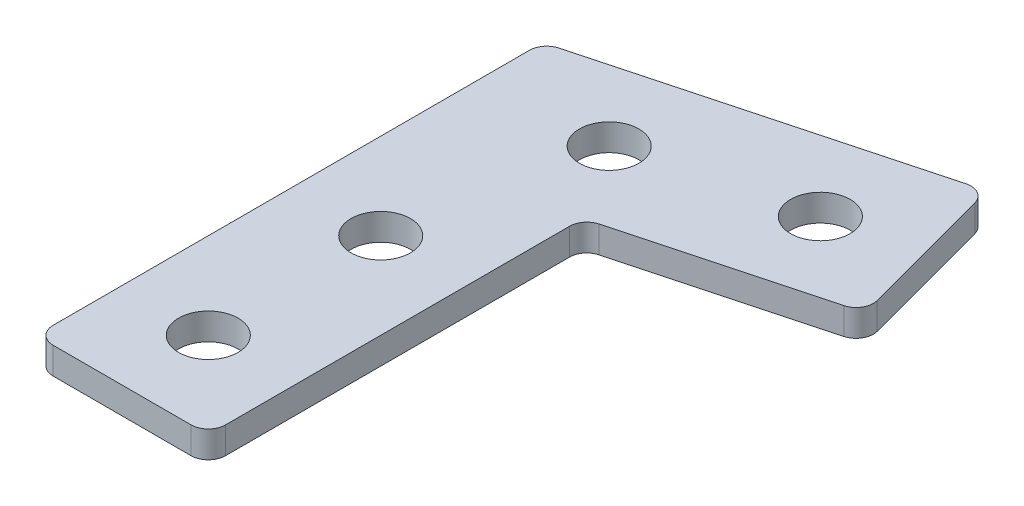
SolidWorks part; units mm, degrees
ref_plane "Front Plane" through (0, 0, 0) normal (0, 0, 1) x (1, 0, 0)
ref_plane "Top Plane" through (0, 0, 0) normal (0, 1, 0) x (1, 0, 0)
ref_plane "Right Plane" through (0, 0, 0) normal (1, 0, 0) x (0, 0, -1)
sketch "Sketch2" plane through (0, 0, 0) normal (0, 1, 0) x (1, 0, 0)
  line L0 (15.3185, 24.8356) -> (-4, 19.6593)
  line L1 (-5, 10) -> (5, 10)
  line L2 (-5, 10) -> (-5, -10)
  line L3 (-5, -10) -> (5, -10)
  line L4 (5, 10) -> (5, -10)
  line L5 (-5, 10) -> (5, -10) construction
  line L6 (-5, -10) -> (5, 10) construction
  line L7 (15.3185, 24.8356) -> (17.9067, 15.1764)
  line L8 (-4, 19.6593) -> (-1.4118, 10)
  line L9 (17.9067, 15.1764) -> (-1.4118, 10)
  line L10 (-2.7059, 14.8296) -> (16.6126, 20.006) construction
  line L11 (-4, 19.6593) -> (-5, 19.3913)
  line L12 (5, 10) -> (5, 11.718)
  line L13 (-5, 19.3913) -> (-5, 10)
  circle A0 centre (0, -5) radius 1.725
  circle A1 centre (0, 5) radius 1.725
  circle A2 centre (2.1237, 16.1237) radius 1.725
  circle A3 centre (11.783, 18.7119) radius 1.725
  point P0 (0, 0)
  dimension "D3" = 3.45
  dimension "D4" = 5
  dimension "D1" = 10
  dimension "D2" = 20
  dimension "D5" = 10
  dimension "D6" = 105
  dimension "D7" = 10
  dimension "D8" = 20
  dimension "D9" = 5
  dimension "D10" = 10
  dimension "D11" = 1
extrude "Boss-Extrude1" add sketch "Sketch2" along normal blind 1.55
fillet "Fillet1" radius 1 6 edges at (15.3185, 0.775, -24.8356) (17.9067, 0.775, -15.1764) (5, 0.775, -11.718) (5, 0.775, 10) (-5, 0.775, 10) (-5, 0.775, -19.3913)
